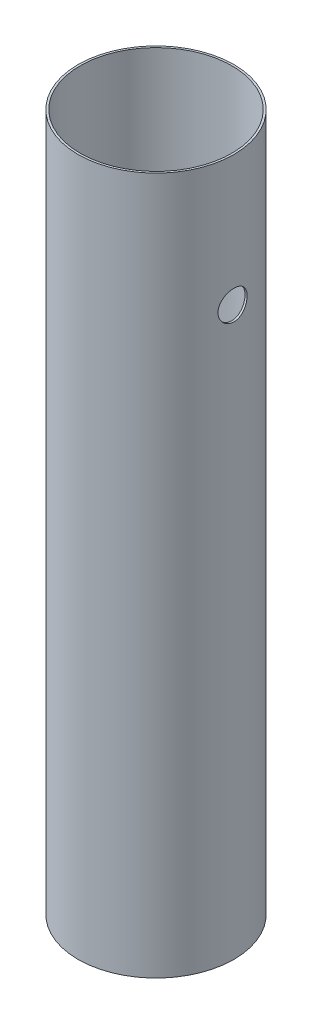
SolidWorks part; units mm, degrees
material "PVC Rígido"
ref_plane "Alzado" through (0, 0, 0) normal (0, 0, 1) x (1, 0, 0)
ref_plane "Planta" through (0, 0, 0) normal (0, 1, 0) x (1, 0, 0)
ref_plane "Vista lateral" through (0, 0, 0) normal (1, 0, 0) x (0, 0, -1)
sketch "Croquis1" plane through (0, 0, 0) normal (0, 1, 0) x (1, 0, 0)
  circle A0 centre (0, 0) radius 55.5
  circle A1 centre (0, 0) radius 57
  dimension "D1" = 111
  dimension "D2" = 114
extrude "Saliente-Extruir1" add sketch "Croquis1" along normal blind 510
ref_plane "Plano1" through (57, 0, 0) normal (1, 0, 0) x (0, 0, -1)
sketch "Croquis2" plane through (57, 0, 0) normal (1, 0, 0) x (0, 0, -1)
  line L0 (-57, 0) -> (57, 0) construction
  circle A0 centre (0, 414.6) radius 10.65
  dimension "D1" = 21.3
  dimension "D2" = 414.6
extrude "Cortar-Extruir1" cut sketch "Croquis2" against normal blind 10
